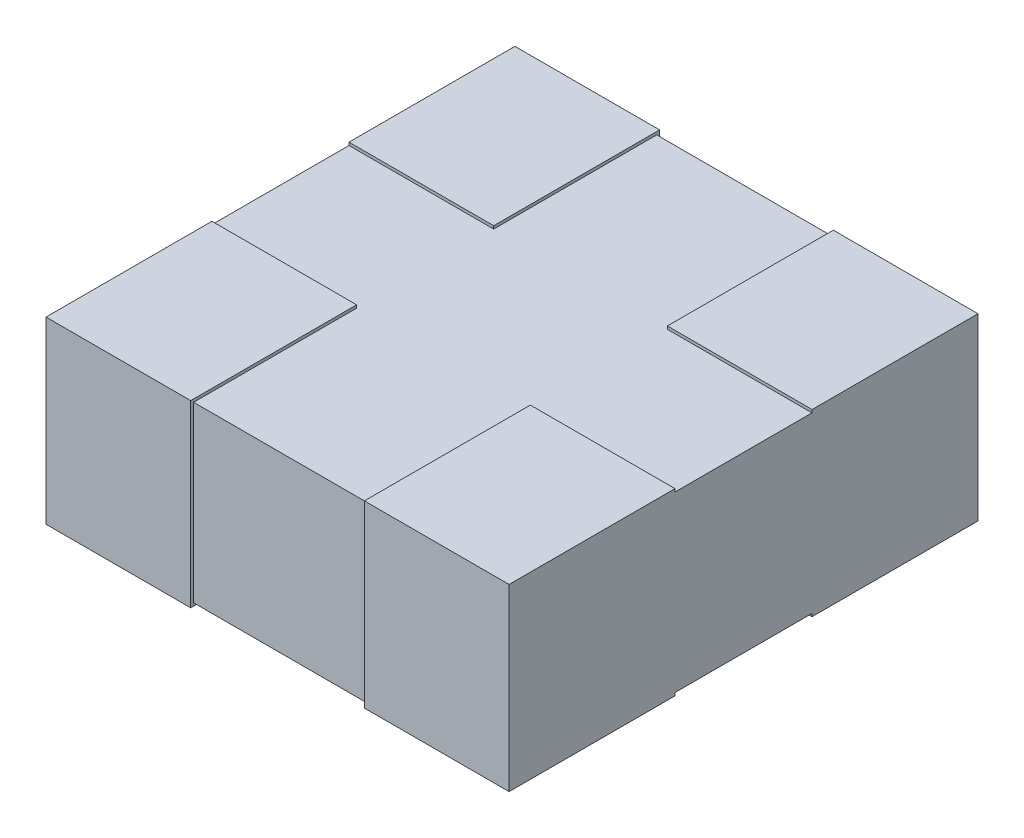
SolidWorks part; units mm, degrees
ref_plane "前视基准面" through (0, 0, 0) normal (0, 0, 1) x (1, 0, 0)
ref_plane "上视基准面" through (0, 0, 0) normal (0, 1, 0) x (1, 0, 0)
ref_plane "右视基准面" through (0, 0, 0) normal (1, 0, 0) x (0, 0, -1)
sketch "草图1" plane through (0, 0, 0) normal (0, 1, 0) x (1, 0, 0)
  line L0 (-3.4256, 0) -> (1.6422, 0) construction
  line L1 (-0.8, 0.8) -> (0.8, 0.8)
  line L2 (-0.8, 0.8) -> (-0.8, -0.8)
  line L3 (-0.8, -0.8) -> (0.8, -0.8)
  line L4 (0.8, 0.8) -> (0.8, -0.8)
  line L5 (0, 2.0678) -> (0, -1.7918) construction
  dimension "D1" = 1.6
  dimension "D2" = 1.6
extrude "凸台-拉伸1" add sketch "草图1" along normal blind 0.6
sketch "草图2" plane through (-0.8, 0, 0) normal (-1, 0, 0) x (0, 0, 1)
  line L0 (0, 0.6734) -> (0, -0.2179) construction
  line L1 (0.81, 0.61) -> (0.81, -0.01)
  line L2 (0.2367, 0.61) -> (0.81, 0.61)
  line L3 (0.2367, -0.01) -> (0.2367, 0.61)
  line L4 (0.81, -0.01) -> (0.2367, -0.01)
  line L8 (-0.81, -0.01) -> (0.81, -0.01)
  line L9 (0.81, -0.01) -> (0.81, 0.61)
  line L10 (0.81, 0.61) -> (-0.81, 0.61)
  line L11 (-0.81, 0.61) -> (-0.81, -0.01)
  line L12 (-0.81, -0.01) -> (-0.2367, -0.01)
  line L13 (-0.2367, -0.01) -> (-0.2367, 0.61)
  line L14 (-0.2367, 0.61) -> (-0.81, 0.61)
  line L15 (-0.81, 0.61) -> (-0.81, -0.01)
  dimension "D1" = 0.01
extrude "凸台-拉伸2" add sketch "草图2" against normal blind 0.5
mirror "镜向1" about plane through (0, 0, 0) normal (1, 0, 0) of "凸台-拉伸2"
